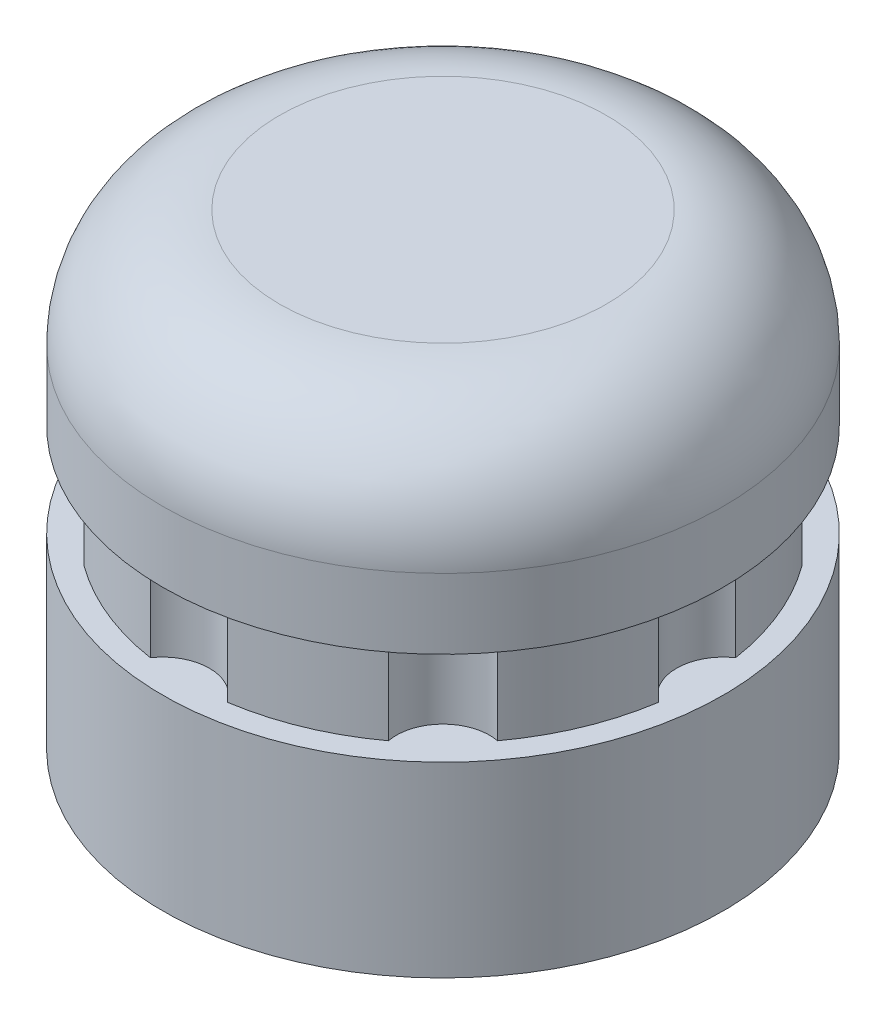
SolidWorks part; units mm, degrees
material "ABS"
ref_plane "Alzado" through (0, 0, 0) normal (0, 0, 1) x (1, 0, 0)
ref_plane "Planta" through (0, 0, 0) normal (0, 1, 0) x (1, 0, 0)
ref_plane "Vista lateral" through (0, 0, 0) normal (1, 0, 0) x (0, 0, -1)
sketch "Croquis12" plane through (0, 0, 0) normal (0, 1, 0) x (1, 0, 0)
  line L0 (0, 0) -> (0, -19.2009) construction
  circle A0 centre (0, 0) radius 12
  circle A1 centre (0, -12) radius 2
  circle A2 centre (-8.4853, -8.4853) radius 2
  circle A3 centre (-12, 0) radius 2
  circle A4 centre (-8.4853, 8.4853) radius 2
  circle A5 centre (0, 12) radius 2
  circle A6 centre (8.4853, 8.4853) radius 2
  circle A7 centre (12, 0) radius 2
  circle A8 centre (8.4853, -8.4853) radius 2
  circle A9 centre (0, 0) radius 11
  point P23 (0, 0)
  dimension "D1" = 8
extrude "Saliente-Extruir3" add sketch "Croquis12" along normal blind 20
sketch "Croquis13" plane through (0, 0, 0) normal (0, -1, 0) x (1, 0, 0)
  circle A0 centre (0, 0) radius 12
extrude "Saliente-Extruir4" add sketch "Croquis13" against normal blind 8
sketch "Croquis15" plane through (0, 20, 0) normal (0, 1, 0) x (1, 0, 0)
  circle A0 centre (0, 0) radius 12
extrude "Saliente-Extruir5" add sketch "Croquis15" against normal blind 8
sketch "Croquis16" plane through (0, 0, 0) normal (0, -1, 0) x (1, 0, 0)
  circle A0 centre (0, 0) radius 5
extrude "Cortar-Extruir6" cut sketch "Croquis16" against normal blind 2
sketch "Croquis17" plane through (0, 2, 0) normal (0, -1, 0) x (1, 0, 0)
  circle A0 centre (0, 0) radius 2.5
extrude "Cortar-Extruir7" cut sketch "Croquis17" against normal blind 2
sketch "Croquis18" plane through (0, 4, 0) normal (0, -1, 0) x (1, 0, 0)
  line L0 (-1.5, 2) -> (-1.5, -2)
  line L1 (1.5, 2) -> (1.5, -2)
  arc A0 (-1.5, -2) -> (1.5, -2) centre (0, 0) ccw
  arc A1 (1.5, 2) -> (-1.5, 2) centre (0, 0) ccw
  dimension "D1" = 1.5
  dimension "D2" = 3
extrude "Cortar-Extruir8" cut sketch "Croquis18" against normal blind 7
fillet "Redondeo2" radius 5 1 edges at (0, 20, 12)
